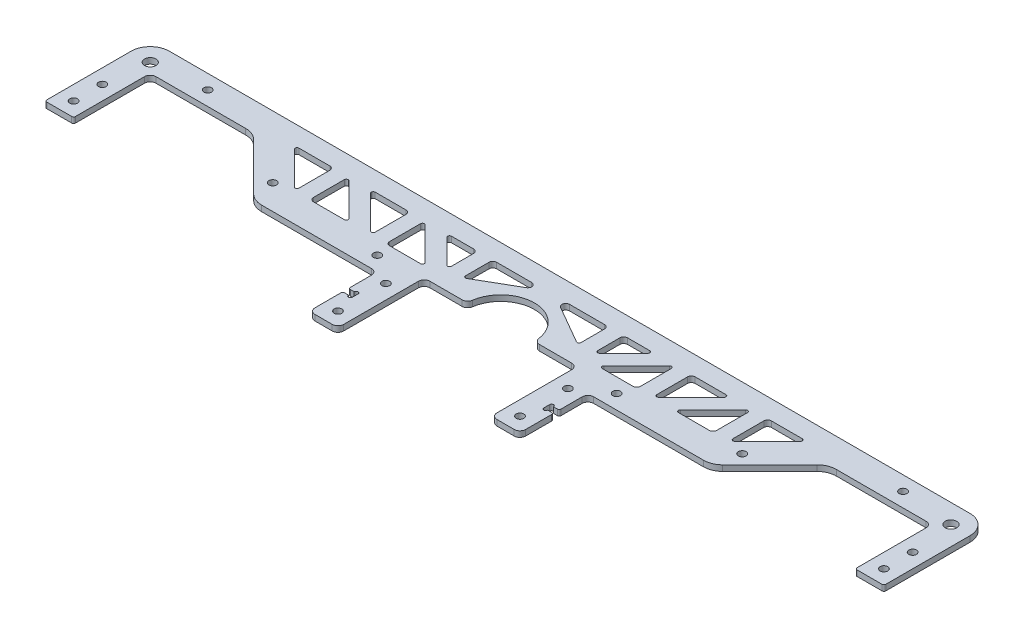
SolidWorks part; units mm, degrees
material "Thornel Mat VMA"
ref_plane "前视基准面" through (0, 0, 0) normal (0, 0, 1) x (1, 0, 0)
ref_plane "上视基准面" through (0, 0, 0) normal (0, 1, 0) x (1, 0, 0)
ref_plane "右视基准面" through (0, 0, 0) normal (1, 0, 0) x (0, 0, -1)
sketch "草图1" plane through (0, 0, 0) normal (0, 1, 0) x (1, 0, 0)
  line L1 (-55, 0) -> (55, 0)
  line L12 (-204, 66) -> (-150, 66)
  line L28 (-209, 81) -> (209, 81)
  line L31 (-150, 66) -> (-119.5, 35.5)
  line L37 (-219, 71) -> (-219, 26)
  line L39 (0, 0) -> (0, 41) construction
  line L41 (219, 71) -> (219, 26)
  line L43 (150, 66) -> (119.5, 35.5)
  line L47 (204, 66) -> (150, 66)
  line L66 (-219, 26) -> (-204, 26)
  line L67 (219, 26) -> (204, 26)
  line L68 (-204, 26) -> (-204, 66)
  line L69 (204, 26) -> (204, 66)
  line L70 (-55, 0) -> (-55, 35.5)
  line L71 (55, 0) -> (55, 35.5)
  line L80 (-119.5, 35.5) -> (-55, 35.5)
  line L81 (119.5, 35.5) -> (55, 35.5)
  line L87 (0, -55) -> (0, 55) construction
  line L89 (-25, 27) -> (25, 27) construction
  line L90 (25, 27) -> (25, -7) construction
  circle A0 centre (-25, 27) radius 2 construction
  circle A1 centre (25, 27) radius 2 construction
  circle A2 centre (25, -7) radius 2 construction
  arc A3 (-219, 71) -> (-209, 81) centre (-209, 71) cw
  arc A4 (219, 71) -> (209, 81) centre (209, 71) ccw
  point P8 (0, 0)
  point P10 (0, 0)
  point P11 (-207.7523, 66)
  point P28 (0, 0)
  point P32 (209.7658, 80.9706)
  dimension "D3" = 81
  dimension "D4" = 35.5
  dimension "D5" = 135
  dimension "D6" = 15
  dimension "D7" = 10
  dimension "D12" = 50
  dimension "D8" = 150
  dimension "D13" = 34
  dimension "D14" = 27
  dimension "D18" = 4
  dimension "D15" = 110
  dimension "D17" = 55
  dimension "D21" = 438
  dimension "D22" = 15
extrude "凸台-拉伸1" add sketch "草图1" along normal blind 3
sketch "草图2" plane through (0, 3, 0) normal (0, 1, 0) x (1, 0, 0)
  line L0 (55, 0) -> (55, 35.5) construction
  line L1 (-47.5, 7.5) -> (-47.5, 32.5) construction
  line L6 (-55, 0) -> (55, 0) construction
  line L7 (-219, 26) -> (-204, 26) construction
  line L8 (-55, 35.5) -> (-55, 0) construction
  line L11 (209, 81) -> (-209, 81) construction
  line L14 (0, -55) -> (0, 55) construction
  line L15 (-40, 0) -> (40, 0)
  line L16 (0, 0) -> (0, 45) construction
  line L17 (-40, 0) -> (-40, 45)
  line L18 (-40, 45) -> (40, 45)
  line L19 (40, 0) -> (40, 45)
  line L20 (-119.5, 35.5) -> (-55, 35.5) construction
  line L21 (-55, 35.5) -> (-55, 0) construction
  line L22 (-204, 66) -> (-150, 66) construction
  line L23 (-219, 71) -> (-219, 26) construction
  line L26 (-55, 35.5) -> (-55, 0) construction
  line L27 (-55, 0) -> (55, 0) construction
  line L29 (50, 17.5) -> (50, 20.5)
  line L30 (55, 17.5) -> (50, 17.5)
  line L31 (55, 20.5) -> (55, 17.5)
  line L32 (50, 20.5) -> (55, 20.5)
  line L33 (-50, 20.5) -> (-55, 20.5)
  line L34 (-55, 20.5) -> (-55, 17.5)
  line L35 (-55, 17.5) -> (-50, 17.5)
  line L36 (-50, 17.5) -> (-50, 20.5)
  circle A10 centre (-47.5, 32.5) radius 2
  circle A18 centre (-211.5, 33.5) radius 2
  circle A19 centre (-211.5, 48.5) radius 2
  circle A36 centre (211.5, 48.5) radius 2
  circle A37 centre (211.5, 33.5) radius 2
  circle A39 centre (-181.5, 73.5) radius 2
  circle A40 centre (181.5, 73.5) radius 2
  circle A45 centre (47.5, 32.5) radius 2
  circle A46 centre (-47.5, 7.5) radius 2
  circle A47 centre (-62.5, 43) radius 2
  circle A48 centre (-122.5, 48.5) radius 2
  circle A49 centre (62.5, 43) radius 2
  circle A50 centre (122.5, 48.5) radius 2
  circle A51 centre (47.5, 7.5) radius 2
  point P29 (-211.5, 26)
  dimension "D3" = 7.5
  dimension "D4" = 25
  dimension "D7" = 15
  dimension "D9" = 4
  dimension "D10" = 15
  dimension "D11" = 59
  dimension "D6" = 7.5
  dimension "D20" = 45
  dimension "D21" = 32.5
  dimension "D22" = 3
  dimension "D23" = 5
  dimension "D24" = 17.5
  dimension "D13" = 4
  dimension "D14" = 4
  dimension "D12" = 7.5
  dimension "D15" = 7.5
  dimension "D16" = 7.5
  dimension "D17" = 37.5
  dimension "D5" = 7.5
  dimension "D18" = 15
extrude "切除-拉伸1" cut sketch "草图2" against normal blind 10
sketch "草图5" plane through (0, 3, 0) normal (0, 1, 0) x (1, 0, 0)
  line L0 (0, -55) -> (0, 55) construction
  line L5 (40, 45) -> (-40, 45) construction
  line L6 (-50, 20.5) -> (-55, 20.5) construction
  line L18 (-55, 17.5) -> (-50, 17.5) construction
  line L26 (-219, 71) -> (-219, 26) construction
  line L29 (209, 81) -> (-209, 81) construction
  circle A16 centre (-209, 71) radius 3
  circle A19 centre (209, 71) radius 3
  circle A20 centre (0, 45) radius 17.5
  circle A21 centre (-51, 20.5) radius 1
  circle A22 centre (-51, 17.5) radius 1
  circle A23 centre (51, 17.5) radius 1
  circle A24 centre (51, 20.5) radius 1
  dimension "D3" = 2
  dimension "D12" = 6
  dimension "D13" = 10
  dimension "D2" = 35
  dimension "D14" = 10
extrude "切除-拉伸4" cut sketch "草图5" against normal through all
sketch "草图6" plane through (0, 3, 0) normal (0, 1, 0) x (1, 0, 0)
  line L0 (-133.7868, 71) -> (-113.2868, 71)
  line L1 (-113.2868, 71) -> (-113.2868, 50.5)
  line L2 (-113.2868, 50.5) -> (-133.7868, 71)
  line L3 (-105.2868, 50.5) -> (-105.2868, 71)
  line L4 (-105.2868, 71) -> (-84.7868, 50.5)
  line L5 (-84.7868, 50.5) -> (-105.2868, 50.5)
  line L6 (-150, 66) -> (-119.5, 35.5) construction
  line L7 (209, 81) -> (-209, 81) construction
  line L8 (-30.1594, 71) -> (-9.9107, 71)
  line L19 (-119.5, 35.5) -> (-55, 35.5) construction
  line L20 (0, -55) -> (0, 55) construction
  line L27 (84.7868, 50.5) -> (105.2868, 50.5)
  line L28 (105.2868, 71) -> (84.7868, 50.5)
  line L29 (105.2868, 50.5) -> (105.2868, 71)
  line L30 (113.2868, 50.5) -> (133.7868, 71)
  line L31 (113.2868, 71) -> (113.2868, 50.5)
  line L32 (133.7868, 71) -> (113.2868, 71)
  line L36 (-8.9107, 67.2679) -> (-30.1594, 55)
  line L37 (-30.1594, 55) -> (-30.1594, 71)
  line L38 (-93.9731, 71) -> (-73.4731, 71)
  line L39 (-73.4731, 71) -> (-73.4731, 50.5)
  line L40 (-73.4731, 50.5) -> (-93.9731, 71)
  line L41 (-65.4731, 50.5) -> (-65.4731, 71)
  line L42 (-65.4731, 71) -> (-44.9731, 50.5)
  line L43 (-44.9731, 50.5) -> (-65.4731, 50.5)
  line L44 (-54.1594, 71) -> (-38.1594, 71)
  line L45 (-38.1594, 71) -> (-38.1594, 55)
  line L46 (-38.1594, 55) -> (-54.1594, 71)
  line L50 (-17.5, 45) -> (-40, 45) construction
  line L53 (38.1594, 55) -> (54.1594, 71)
  line L54 (38.1594, 71) -> (38.1594, 55)
  line L55 (54.1594, 71) -> (38.1594, 71)
  line L56 (44.9731, 50.5) -> (65.4731, 50.5)
  line L57 (65.4731, 71) -> (44.9731, 50.5)
  line L58 (65.4731, 50.5) -> (65.4731, 71)
  line L59 (73.4731, 50.5) -> (93.9731, 71)
  line L60 (73.4731, 71) -> (73.4731, 50.5)
  line L61 (93.9731, 71) -> (73.4731, 71)
  line L62 (30.1594, 55) -> (30.1594, 71)
  line L63 (8.9107, 67.2679) -> (30.1594, 55)
  line L64 (30.1594, 71) -> (9.9107, 71)
  arc A0 (-8.9107, 67.2679) -> (-9.9107, 71) centre (-9.9107, 69) ccw
  arc A1 (8.9107, 67.2679) -> (9.9107, 71) centre (9.9107, 69) cw
  dimension "D11" = 2
  dimension "D1" = 15
  dimension "D2" = 10
  dimension "D3" = 15
  dimension "D4" = 8
  dimension "D5" = 8
  dimension "D6" = 8
  dimension "D7" = 8
  dimension "D8" = 10
  dimension "D9" = 8
  dimension "D10" = 60
extrude "切除-拉伸5" cut sketch "草图6" against normal through all
fillet "圆角1" radius 10 4 edges at (-150, 1.5, -66) (150, 1.5, -66) (-119.5, 1.5, -35.5) (119.5, 1.5, -35.5)
fillet "圆角2" radius 3 12 edges at (40, 1.5, -45) (55, 1.5, 0) (40, 1.5, 0) (-55, 1.5, 0) (-40, 1.5, 0) (-40, 1.5, -45) (-55, 1.5, -35.5) (55, 1.5, -35.5) (17.5, 1.5, -45) (-17.5, 1.5, -45) (204, 1.5, -66) (-204, 1.5, -66)
chamfer "倒角1" [suppressed] distance 2.5 distance2 2
chamfer "倒角2" [suppressed] distance 7.5 distance2 12
chamfer "倒角3" [suppressed] distance 12 distance2 7.5
fillet "圆角3" radius 1 30 edges at (55, 1.5, -17.5) (55, 1.5, -20.5) (-55, 1.5, -17.5) (-55, 1.5, -20.5) (219, 1.5, -26) (204, 1.5, -26) (-204, 1.5, -26) (-219, 1.5, -26) (-65.4731, 1.5, -71) (-44.9731, 1.5, -50.5) (54.1594, 1.5, -71) (38.1594, 1.5, -55) (44.9731, 1.5, -50.5) (65.4731, 1.5, -71) (93.9731, 1.5, -71) (73.4731, 1.5, -50.5) (-105.2868, 1.5, -71) (-84.7868, 1.5, -50.5) (-30.1594, 1.5, -55) (-73.4731, 1.5, -50.5) (-93.9731, 1.5, -71) (-38.1594, 1.5, -55) (-54.1594, 1.5, -71) (30.1594, 1.5, -55) (84.7868, 1.5, -50.5) (105.2868, 1.5, -71) (133.7868, 1.5, -71) (113.2868, 1.5, -50.5) (-113.2868, 1.5, -50.5) (-133.7868, 1.5, -71)
fillet "圆角4" radius 2 12 edges at (113.2868, 1.5, -71) (105.2868, 1.5, -50.5) (73.4731, 1.5, -71) (65.4731, 1.5, -50.5) (38.1594, 1.5, -71) (30.1594, 1.5, -71) (-30.1594, 1.5, -71) (-38.1594, 1.5, -71) (-65.4731, 1.5, -50.5) (-73.4731, 1.5, -71) (-105.2868, 1.5, -50.5) (-113.2868, 1.5, -71)
